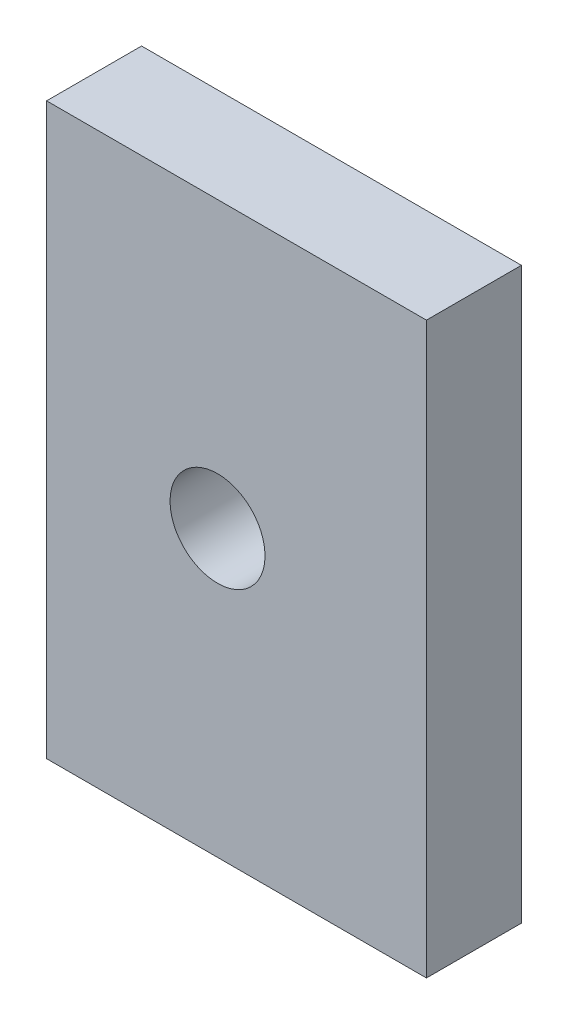
SolidWorks part; units mm, degrees
ref_plane "Front Plane" through (0, 0, 0) normal (0, 0, 1) x (1, 0, 0)
ref_plane "Top Plane" through (0, 0, 0) normal (0, 1, 0) x (1, 0, 0)
ref_plane "Right Plane" through (0, 0, 0) normal (1, 0, 0) x (0, 0, -1)
sketch "Sketch1" plane through (0, 0, 0) normal (0, 0, 1) x (1, 0, 0)
  line L1 (-10, -15) -> (10, -15)
  line L2 (-10, -15) -> (-10, 15)
  line L3 (-10, 15) -> (10, 15)
  line L4 (10, -15) -> (10, 15)
  line L5 (-10, -15) -> (10, 15) construction
  line L6 (-10, 15) -> (10, -15) construction
  point P0 (0, 0)
  dimension "D1" = 20
  dimension "D2" = 30
extrude "Boss-Extrude1" add sketch "Sketch1" along normal blind 5
sketch "Sketch2" plane through (0, 0, 5) normal (0, 0, 1) x (1, 0, 0)
  line L0 (-10, 15) -> (-10, -15) construction
  circle A0 centre (-1, 0) radius 2.5
  dimension "D1" = 5
  dimension "D2" = 9
extrude "Cut-Extrude1" cut sketch "Sketch2" against normal blind 9 and the other way blind 12
